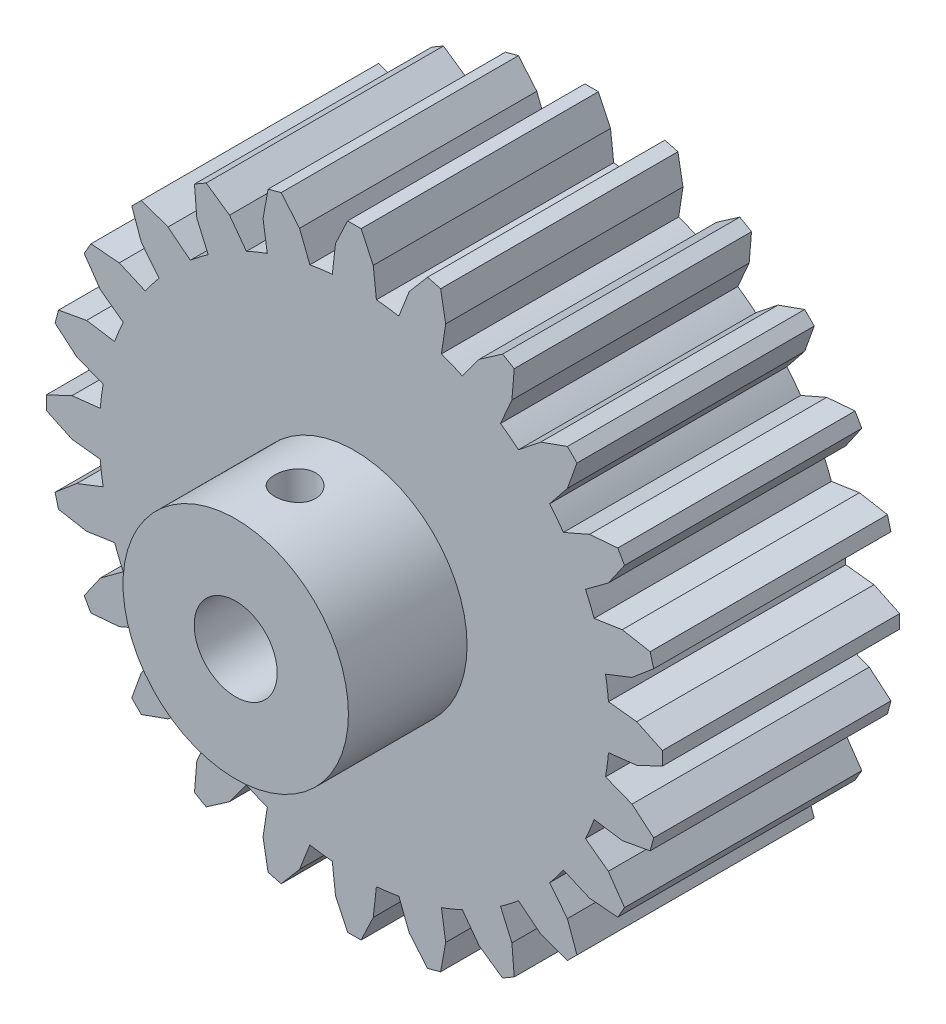
SolidWorks part; units mm, degrees
ref_plane "Plan de face" through (0, 0, 0) normal (0, 0, 1) x (1, 0, 0)
ref_plane "Plan de dessus" through (0, 0, 0) normal (0, 1, 0) x (1, 0, 0)
ref_plane "Plan de droite" through (0, 0, 0) normal (1, 0, 0) x (0, 0, -1)
sketch "Esquisse1" plane through (0, 0, 0) normal (0, 0, 1) x (1, 0, 0)
  line L0 (-1.8585, 21.4195) -> (-1.5915, 23.7996)
  line L1 (0, 2.2889) -> (0, 19223.5431) construction
  line L2 (-1.5915, 23.7996) -> (-0.5695, 25.9656)
  line L3 (-0.5695, 25.9656) -> (0.5695, 25.9656)
  line L4 (0, 0) -> (50000, 0) construction
  line L5 (1.8585, 21.4195) -> (1.5915, 23.7996)
  line L6 (1.5915, 23.7996) -> (0.5695, 25.9656)
  line L7 (3.7486, 21.1707) -> (4.6225, 23.4006)
  line L8 (4.6225, 23.4006) -> (6.1703, 25.2282)
  line L9 (7.6971, 22.5767) -> (7.2705, 24.9334)
  line L10 (7.339, 20.2087) -> (7.6971, 22.5767)
  line L11 (6.1703, 25.2282) -> (7.2705, 24.9334)
  line L12 (9.1003, 19.4791) -> (10.5215, 21.4068)
  line L13 (10.5215, 21.4068) -> (12.4896, 22.7716)
  line L14 (13.2781, 19.8153) -> (13.476, 22.2021)
  line L15 (12.3193, 17.6206) -> (13.2781, 19.8153)
  line L16 (12.4896, 22.7716) -> (13.476, 22.2021)
  line L17 (13.8317, 16.46) -> (15.7035, 17.9542)
  line L18 (15.7035, 17.9542) -> (17.9577, 18.7631)
  line L19 (17.9542, 15.7035) -> (18.7631, 17.9577)
  line L20 (16.46, 13.8317) -> (17.9542, 15.7035)
  line L21 (17.9577, 18.7631) -> (18.7631, 17.9577)
  line L22 (17.6206, 12.3193) -> (19.8153, 13.2781)
  line L23 (19.8153, 13.2781) -> (22.2021, 13.476)
  line L24 (21.4068, 10.5215) -> (22.7716, 12.4896)
  line L25 (19.4791, 9.1003) -> (21.4068, 10.5215)
  line L26 (22.2021, 13.476) -> (22.7716, 12.4896)
  line L27 (20.2087, 7.339) -> (22.5767, 7.6971)
  line L28 (22.5767, 7.6971) -> (24.9334, 7.2705)
  line L29 (23.4006, 4.6225) -> (25.2282, 6.1703)
  line L30 (21.1707, 3.7486) -> (23.4006, 4.6225)
  line L31 (24.9334, 7.2705) -> (25.2282, 6.1703)
  line L32 (21.4195, 1.8585) -> (23.7996, 1.5915)
  line L33 (23.7996, 1.5915) -> (25.9656, 0.5695)
  line L34 (23.7996, -1.5915) -> (25.9656, -0.5695)
  line L35 (21.4195, -1.8585) -> (23.7996, -1.5915)
  line L36 (25.9656, 0.5695) -> (25.9656, -0.5695)
  line L37 (21.1707, -3.7486) -> (23.4006, -4.6225)
  line L38 (23.4006, -4.6225) -> (25.2282, -6.1703)
  line L39 (22.5767, -7.6971) -> (24.9334, -7.2705)
  line L40 (20.2087, -7.339) -> (22.5767, -7.6971)
  line L41 (25.2282, -6.1703) -> (24.9334, -7.2705)
  line L42 (19.4791, -9.1003) -> (21.4068, -10.5215)
  line L43 (21.4068, -10.5215) -> (22.7716, -12.4896)
  line L44 (19.8153, -13.2781) -> (22.2021, -13.476)
  line L45 (17.6206, -12.3193) -> (19.8153, -13.2781)
  line L46 (22.7716, -12.4896) -> (22.2021, -13.476)
  line L47 (16.46, -13.8317) -> (17.9542, -15.7035)
  line L48 (17.9542, -15.7035) -> (18.7631, -17.9577)
  line L49 (15.7035, -17.9542) -> (17.9577, -18.7631)
  line L50 (13.8317, -16.46) -> (15.7035, -17.9542)
  line L51 (18.7631, -17.9577) -> (17.9577, -18.7631)
  line L52 (12.3193, -17.6206) -> (13.2781, -19.8153)
  line L53 (13.2781, -19.8153) -> (13.476, -22.2021)
  line L54 (10.5215, -21.4068) -> (12.4896, -22.7716)
  line L55 (9.1003, -19.4791) -> (10.5215, -21.4068)
  line L56 (13.476, -22.2021) -> (12.4896, -22.7716)
  line L57 (7.339, -20.2087) -> (7.6971, -22.5767)
  line L58 (7.6971, -22.5767) -> (7.2705, -24.9334)
  line L59 (4.6225, -23.4006) -> (6.1703, -25.2282)
  line L60 (3.7486, -21.1707) -> (4.6225, -23.4006)
  line L61 (7.2705, -24.9334) -> (6.1703, -25.2282)
  line L62 (1.8585, -21.4195) -> (1.5915, -23.7996)
  line L63 (1.5915, -23.7996) -> (0.5695, -25.9656)
  line L64 (-1.5915, -23.7996) -> (-0.5695, -25.9656)
  line L65 (-1.8585, -21.4195) -> (-1.5915, -23.7996)
  line L66 (0.5695, -25.9656) -> (-0.5695, -25.9656)
  line L67 (-3.7486, -21.1707) -> (-4.6225, -23.4006)
  line L68 (-4.6225, -23.4006) -> (-6.1703, -25.2282)
  line L69 (-7.6971, -22.5767) -> (-7.2705, -24.9334)
  line L70 (-7.339, -20.2087) -> (-7.6971, -22.5767)
  line L71 (-6.1703, -25.2282) -> (-7.2705, -24.9334)
  line L72 (-9.1003, -19.4791) -> (-10.5215, -21.4068)
  line L73 (-10.5215, -21.4068) -> (-12.4896, -22.7716)
  line L74 (-13.2781, -19.8153) -> (-13.476, -22.2021)
  line L75 (-12.3193, -17.6206) -> (-13.2781, -19.8153)
  line L76 (-12.4896, -22.7716) -> (-13.476, -22.2021)
  line L77 (-13.8317, -16.46) -> (-15.7035, -17.9542)
  line L78 (-15.7035, -17.9542) -> (-17.9577, -18.7631)
  line L79 (-17.9542, -15.7035) -> (-18.7631, -17.9577)
  line L80 (-16.46, -13.8317) -> (-17.9542, -15.7035)
  line L81 (-17.9577, -18.7631) -> (-18.7631, -17.9577)
  line L82 (-17.6206, -12.3193) -> (-19.8153, -13.2781)
  line L83 (-19.8153, -13.2781) -> (-22.2021, -13.476)
  line L84 (-21.4068, -10.5215) -> (-22.7716, -12.4896)
  line L85 (-19.4791, -9.1003) -> (-21.4068, -10.5215)
  line L86 (-22.2021, -13.476) -> (-22.7716, -12.4896)
  line L87 (-20.2087, -7.339) -> (-22.5767, -7.6971)
  line L88 (-22.5767, -7.6971) -> (-24.9334, -7.2705)
  line L89 (-23.4006, -4.6225) -> (-25.2282, -6.1703)
  line L90 (-21.1707, -3.7486) -> (-23.4006, -4.6225)
  line L91 (-24.9334, -7.2705) -> (-25.2282, -6.1703)
  line L92 (-21.4195, -1.8585) -> (-23.7996, -1.5915)
  line L93 (-23.7996, -1.5915) -> (-25.9656, -0.5695)
  line L94 (-23.7996, 1.5915) -> (-25.9656, 0.5695)
  line L95 (-21.4195, 1.8585) -> (-23.7996, 1.5915)
  line L96 (-25.9656, -0.5695) -> (-25.9656, 0.5695)
  line L97 (-21.1707, 3.7486) -> (-23.4006, 4.6225)
  line L98 (-23.4006, 4.6225) -> (-25.2282, 6.1703)
  line L99 (-22.5767, 7.6971) -> (-24.9334, 7.2705)
  line L100 (-20.2087, 7.339) -> (-22.5767, 7.6971)
  line L101 (-25.2282, 6.1703) -> (-24.9334, 7.2705)
  line L102 (-19.4791, 9.1003) -> (-21.4068, 10.5215)
  line L103 (-21.4068, 10.5215) -> (-22.7716, 12.4896)
  line L104 (-19.8153, 13.2781) -> (-22.2021, 13.476)
  line L105 (-17.6206, 12.3193) -> (-19.8153, 13.2781)
  line L106 (-22.7716, 12.4896) -> (-22.2021, 13.476)
  line L107 (-16.46, 13.8317) -> (-17.9542, 15.7035)
  line L108 (-17.9542, 15.7035) -> (-18.7631, 17.9577)
  line L109 (-15.7035, 17.9542) -> (-17.9577, 18.7631)
  line L110 (-13.8317, 16.46) -> (-15.7035, 17.9542)
  line L111 (-18.7631, 17.9577) -> (-17.9577, 18.7631)
  line L112 (-12.3193, 17.6206) -> (-13.2781, 19.8153)
  line L113 (-13.2781, 19.8153) -> (-13.476, 22.2021)
  line L114 (-10.5215, 21.4068) -> (-12.4896, 22.7716)
  line L115 (-9.1003, 19.4791) -> (-10.5215, 21.4068)
  line L116 (-13.476, 22.2021) -> (-12.4896, 22.7716)
  line L117 (-7.339, 20.2087) -> (-7.6971, 22.5767)
  line L118 (-7.6971, 22.5767) -> (-7.2705, 24.9334)
  line L119 (-4.6225, 23.4006) -> (-6.1703, 25.2282)
  line L120 (-3.7486, 21.1707) -> (-4.6225, 23.4006)
  line L121 (-7.2705, 24.9334) -> (-6.1703, 25.2282)
  arc A0 (-7.339, 20.2087) -> (-9.1003, 19.4791) centre (0, 0) ccw
  circle A1 centre (0, 0) radius 3.5
  arc A2 (-1.8585, 21.4195) -> (-3.7486, 21.1707) centre (0, 0) ccw
  arc A3 (3.7486, 21.1707) -> (1.8585, 21.4195) centre (0, 0) ccw
  arc A4 (9.1003, 19.4791) -> (7.339, 20.2087) centre (0, 0) ccw
  arc A5 (13.8317, 16.46) -> (12.3193, 17.6206) centre (0, 0) ccw
  arc A6 (17.6206, 12.3193) -> (16.46, 13.8317) centre (0, 0) ccw
  arc A7 (20.2087, 7.339) -> (19.4791, 9.1003) centre (0, 0) ccw
  arc A8 (21.4195, 1.8585) -> (21.1707, 3.7486) centre (0, 0) ccw
  arc A9 (21.1707, -3.7486) -> (21.4195, -1.8585) centre (0, 0) ccw
  arc A10 (19.4791, -9.1003) -> (20.2087, -7.339) centre (0, 0) ccw
  arc A11 (16.46, -13.8317) -> (17.6206, -12.3193) centre (0, 0) ccw
  arc A12 (12.3193, -17.6206) -> (13.8317, -16.46) centre (0, 0) ccw
  arc A13 (7.339, -20.2087) -> (9.1003, -19.4791) centre (0, 0) ccw
  arc A14 (1.8585, -21.4195) -> (3.7486, -21.1707) centre (0, 0) ccw
  arc A15 (-3.7486, -21.1707) -> (-1.8585, -21.4195) centre (0, 0) ccw
  arc A16 (-9.1003, -19.4791) -> (-7.339, -20.2087) centre (0, 0) ccw
  arc A17 (-13.8317, -16.46) -> (-12.3193, -17.6206) centre (0, 0) ccw
  arc A18 (-17.6206, -12.3193) -> (-16.46, -13.8317) centre (0, 0) ccw
  arc A19 (-20.2087, -7.339) -> (-19.4791, -9.1003) centre (0, 0) ccw
  arc A20 (-21.4195, -1.8585) -> (-21.1707, -3.7486) centre (0, 0) ccw
  arc A21 (-21.1707, 3.7486) -> (-21.4195, 1.8585) centre (0, 0) ccw
  arc A22 (-19.4791, 9.1003) -> (-20.2087, 7.339) centre (0, 0) ccw
  arc A23 (-16.46, 13.8317) -> (-17.6206, 12.3193) centre (0, 0) ccw
  arc A24 (-12.3193, 17.6206) -> (-13.8317, 16.46) centre (0, 0) ccw
  point P17 (0, 25.9656)
  point P156 (0, 0)
  dimension "D1" = 43
  dimension "D2" = 7
  dimension "D3" = 2.395
  dimension "D4" = 83.6
  dimension "D5" = 1.8585
  dimension "D6" = 2.395
  dimension "D7" = 0.5695
  dimension "D8" = 24
extrude "Boss.-Extru.1" add sketch "Esquisse1" along normal blind 20
sketch "Esquisse2" plane through (0, 0, 20) normal (0, 0, 1) x (1, 0, 0)
  circle A0 centre (0, 0) radius 3.5
  circle A1 centre (0, 0) radius 9.5
  circle A2 centre (0, 0) radius 3.5 construction
  dimension "D1" = 6
extrude "Boss.-Extru.2" add sketch "Esquisse2" along normal blind 10
sketch "Esquisse3" plane through (0, 0, 0) normal (0, 1, 0) x (1, 0, 0)
  line L0 (-7.5, -25) -> (49992.5, -25) construction
  line L1 (-9.5, -20) -> (-9.5, -30) construction
  line L2 (0, -30) -> (0, 49970) construction
  line L3 (-9.5, -30) -> (9.5, -30) construction
  circle A0 centre (0, -25) radius 1.725
  point P6 (-9.5, -25)
  point P13 (0, -30)
  dimension "D1" = 3.45
extrude "Enlèv. mat.-Extru.1" cut sketch "Esquisse3" along normal blind 10
